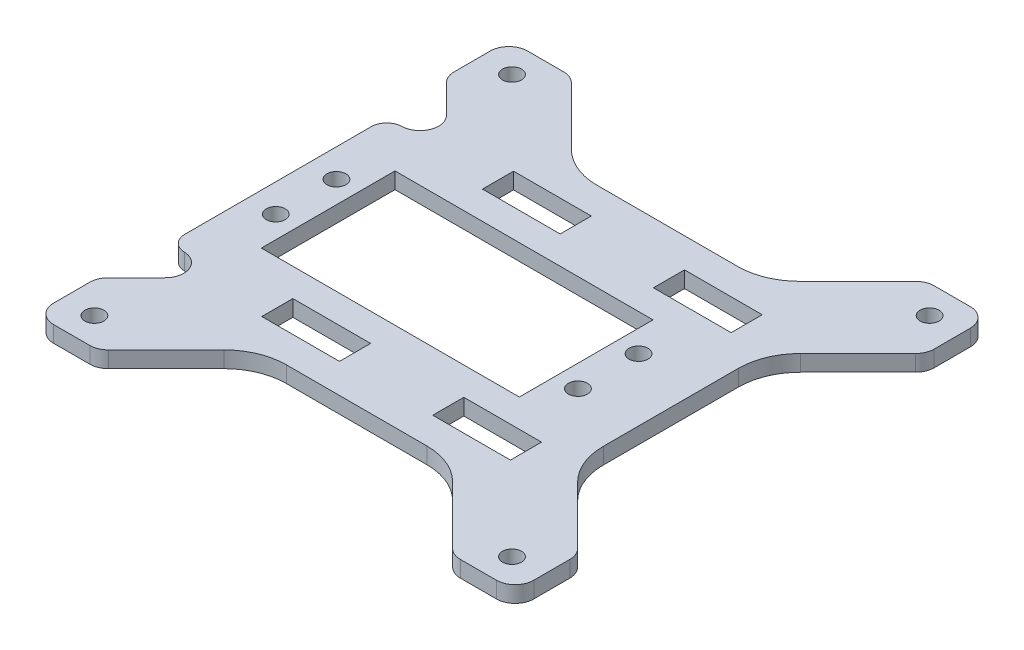
SolidWorks part; units mm, degrees
ref_plane "前视基准面" through (0, 0, 0) normal (0, 0, 1) x (1, 0, 0)
ref_plane "上视基准面" through (0, 0, 0) normal (0, 1, 0) x (1, 0, 0)
ref_plane "右视基准面" through (0, 0, 0) normal (1, 0, 0) x (0, 0, -1)
ref_plane "基准面1" through (0, 0, 0) normal (0, -1, 0) x (1, 0, 0)
sketch "草图1" plane through (0, 0, 0) normal (0, -1, 0) x (1, 0, 0)
  line L0 (18.7279, -17.5) -> (33.0721, -17.5)
  line L1 (33.0721, -17.5) -> (33.0721, -23.2377)
  line L2 (33.0721, -23.2377) -> (18.7279, -23.2377)
  line L3 (18.7279, -23.2377) -> (18.7279, -17.5)
  line L4 (1.5148, 17.5) -> (-12.8295, 17.5)
  line L5 (-12.8295, 17.5) -> (-12.8295, 23.2377)
  line L6 (-12.8295, 23.2377) -> (1.5148, 23.2377)
  line L7 (1.5148, 23.2377) -> (1.5148, 17.5)
  line L8 (23.8115, -12.3361) -> (-23.8115, -12.3361)
  line L9 (-23.8115, -12.3361) -> (-23.8115, 12.3361)
  line L10 (-23.8115, 12.3361) -> (23.8115, 12.3361)
  line L11 (23.8115, 12.3361) -> (23.8115, -12.3361)
  line L12 (-27.9441, -25.9589) -> (-33.1799, -31.1946)
  line L13 (-34.1882, -33.6289) -> (-34.1882, -40.2931)
  line L14 (-30.7456, -43.7357) -> (-24.0814, -43.7357)
  line L15 (-21.6471, -42.7274) -> (-10.9693, -32.0496)
  line L16 (-2.8549, -28.6885) -> (23.0975, -28.6885)
  line L17 (31.2119, -32.0496) -> (41.8897, -42.7274)
  line L18 (44.324, -43.7357) -> (50.9882, -43.7357)
  line L19 (54.4308, -40.2931) -> (54.4308, -33.6289)
  line L20 (53.4225, -31.1946) -> (42.8021, -20.5742)
  line L21 (39.441, -12.4598) -> (39.441, 12.4598)
  line L22 (42.8021, 20.5742) -> (53.4225, 31.1946)
  line L23 (54.4308, 33.6289) -> (54.4308, 40.2931)
  line L24 (50.9882, 43.7357) -> (44.324, 43.7357)
  line L25 (41.8897, 42.7274) -> (31.2119, 32.0496)
  line L26 (23.0975, 28.6885) -> (-2.8549, 28.6885)
  line L27 (-10.9693, 32.0496) -> (-21.6471, 42.7274)
  line L28 (-24.0814, 43.7357) -> (-30.7456, 43.7357)
  line L29 (-34.1882, 40.2931) -> (-34.1882, 33.6289)
  line L30 (-33.1799, 31.1946) -> (-27.9441, 25.9589)
  line L31 (-33.0779, 17.2154) -> (-33.0779, -17.2154)
  line L32 (33.0721, 17.5) -> (18.7279, 17.5)
  line L33 (18.7279, 17.5) -> (18.7279, 23.2377)
  line L34 (18.7279, 23.2377) -> (33.0721, 23.2377)
  line L35 (33.0721, 23.2377) -> (33.0721, 17.5)
  line L36 (1.5148, -17.5) -> (1.5148, -23.2377)
  line L37 (1.5148, -23.2377) -> (-12.8295, -23.2377)
  line L38 (-12.8295, -23.2377) -> (-12.8295, -17.5)
  line L39 (-12.8295, -17.5) -> (1.5148, -17.5)
  circle A0 centre (48.6644, 38.5431) radius 1.75
  circle A1 centre (-28.4218, -38.5431) radius 1.75
  circle A2 centre (27.8852, 5.5943) radius 1.75
  circle A3 centre (-27.8852, 5.5943) radius 1.75
  arc A4 (-33.0779, -17.2154) -> (-30.286, -20.0832) centre (-30.209, -17.2154) ccw
  arc A5 (-30.286, -20.0832) -> (-27.9441, -25.9589) centre (-30.3784, -23.5246) cw
  arc A6 (-33.1799, -31.1946) -> (-34.1882, -33.6289) centre (-30.7456, -33.6289) ccw
  arc A7 (-34.1882, -40.2931) -> (-30.7456, -43.7357) centre (-30.7456, -40.2931) ccw
  arc A8 (-24.0814, -43.7357) -> (-21.6471, -42.7274) centre (-24.0814, -40.2931) ccw
  arc A9 (-10.9693, -32.0496) -> (-2.8549, -28.6885) centre (-2.8549, -40.1639) cw
  arc A10 (23.0975, -28.6885) -> (31.2119, -32.0496) centre (23.0975, -40.1639) cw
  arc A11 (41.8897, -42.7274) -> (44.324, -43.7357) centre (44.324, -40.2931) ccw
  arc A12 (50.9882, -43.7357) -> (54.4308, -40.2931) centre (50.9882, -40.2931) ccw
  arc A13 (54.4308, -33.6289) -> (53.4225, -31.1946) centre (50.9882, -33.6289) ccw
  arc A14 (42.8021, -20.5742) -> (39.441, -12.4598) centre (50.9164, -12.4598) cw
  arc A15 (39.441, 12.4598) -> (42.8021, 20.5742) centre (50.9164, 12.4598) cw
  arc A16 (53.4225, 31.1946) -> (54.4308, 33.6289) centre (50.9882, 33.6289) ccw
  arc A17 (54.4308, 40.2931) -> (50.9882, 43.7357) centre (50.9882, 40.2931) ccw
  arc A18 (44.324, 43.7357) -> (41.8897, 42.7274) centre (44.324, 40.2931) ccw
  arc A19 (31.2119, 32.0496) -> (23.0975, 28.6885) centre (23.0975, 40.1639) cw
  arc A20 (-2.8549, 28.6885) -> (-10.9693, 32.0496) centre (-2.8549, 40.1639) cw
  arc A21 (-21.6471, 42.7274) -> (-24.0814, 43.7357) centre (-24.0814, 40.2931) ccw
  arc A22 (-30.7456, 43.7357) -> (-34.1882, 40.2931) centre (-30.7456, 40.2931) ccw
  arc A23 (-34.1882, 33.6289) -> (-33.1799, 31.1946) centre (-30.7456, 33.6289) ccw
  arc A24 (-27.9441, 25.9589) -> (-30.286, 20.0832) centre (-30.3784, 23.5246) cw
  arc A25 (-30.286, 20.0832) -> (-33.0779, 17.2154) centre (-30.209, 17.2154) ccw
  circle A26 centre (-27.8852, -5.5943) radius 1.75
  circle A27 centre (27.8852, -5.5943) radius 1.75
  circle A28 centre (48.6644, -38.5431) radius 1.75
  circle A29 centre (-28.4218, 38.5431) radius 1.75
  dimension "D1" = 35
extrude "凸台-拉伸1" add sketch "草图1" against normal blind 3
